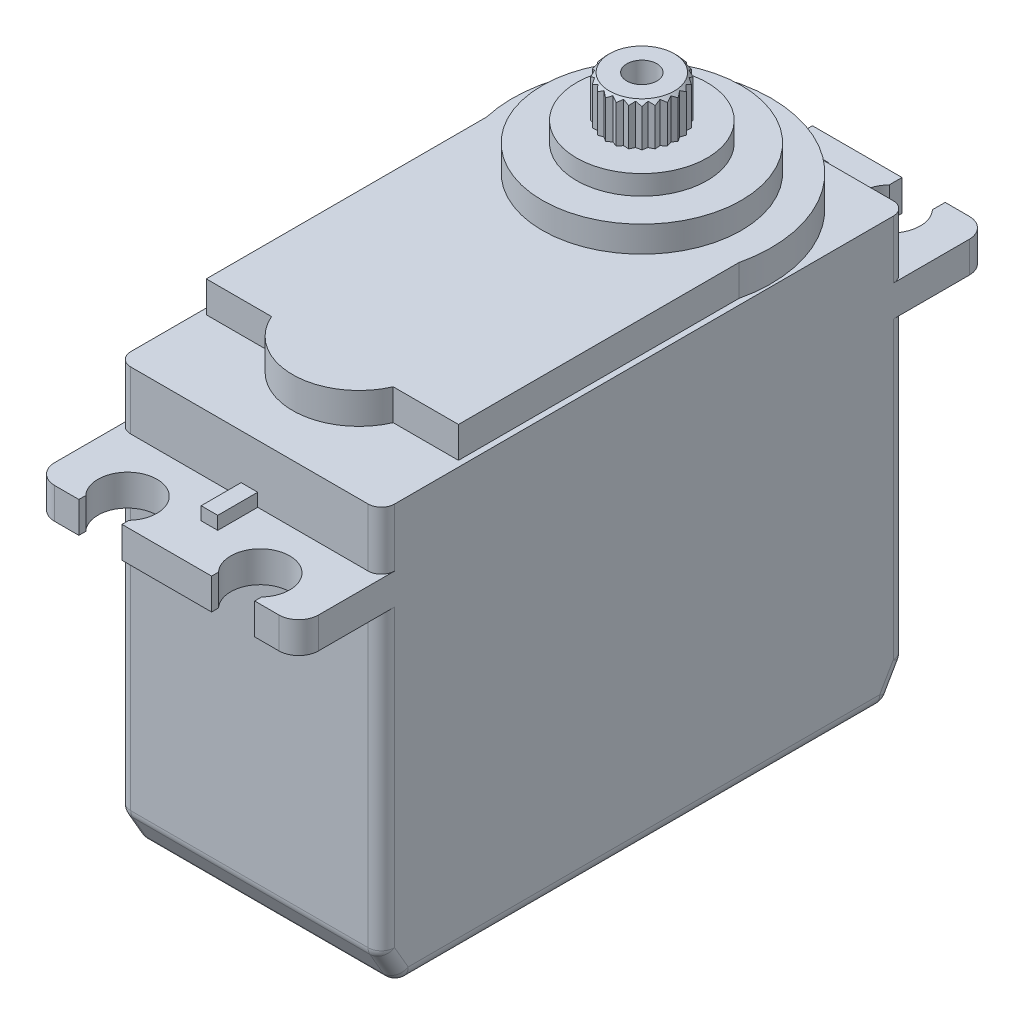
SolidWorks part; units mm, degrees
other "Camera1"
other "Camera2"
other "Camera3"
ref_plane "Front Plane" through (0, 0, 0) normal (0, 0, 1) x (1, 0, 0)
ref_plane "Top Plane" through (0, 0, 0) normal (0, 1, 0) x (1, 0, 0)
ref_plane "Right Plane" through (0, 0, 0) normal (1, 0, 0) x (0, 0, -1)
sketch "Sketch1" plane through (0, 0, 0) normal (0, 1, 0) x (1, 0, 0)
  line L1 (-10.1, 10.16) -> (10.1, 10.16)
  line L2 (-10.1, 10.16) -> (-10.1, -30.04)
  line L3 (-10.1, -30.04) -> (10.1, -30.04)
  line L4 (10.1, 10.16) -> (10.1, -30.04)
  point P4 (0, 10.16)
  dimension "D1" = 20.2
  dimension "D2" = 40.2
  dimension "D4" = 10.16
extrude "Extrude1" add sketch "Sketch1" along normal blind 25.4
sketch "Sketch2" plane through (0, 25.4, 0) normal (0, 1, 0) x (-1, 0, 0)
  line L0 (10.1, 30.04) -> (10.1, 36.3646)
  line L1 (10.1, 36.3646) -> (6.731, 36.3646)
  line L2 (-10.1, 36.3646) -> (-10.1, 30.04)
  line L3 (10.1, -10.16) -> (10.1, -16.4846)
  line L4 (10.1, -10.16) -> (10.1, 30.04)
  line L5 (10.1, 30.04) -> (-10.1, 30.04)
  line L6 (-10.1, 30.04) -> (-10.1, -10.16)
  line L7 (-10.1, -10.16) -> (10.1, -10.16)
  line L8 (10.1, -10.16) -> (10.1, 30.04)
  line L9 (10.1, 30.04) -> (-10.1, 30.04)
  line L10 (-10.1, 30.04) -> (-10.1, -10.16)
  line L11 (-10.1, -10.16) -> (10.1, -10.16)
  line L12 (10.1, -16.4846) -> (6.731, -16.4846)
  line L13 (-10.1, -16.4846) -> (-10.1, -10.16)
  line L14 (-6.731, 35.8342) -> (-6.731, 36.3646)
  line L15 (-3.429, 35.8342) -> (-3.429, 36.3646)
  line L16 (3.429, 35.8342) -> (3.429, 36.3646)
  line L17 (6.731, 35.8342) -> (6.731, 36.3646)
  line L18 (6.731, -15.5142) -> (6.731, -16.4846)
  line L19 (3.429, -15.5142) -> (3.429, -16.4846)
  line L20 (-3.429, -15.5142) -> (-3.429, -16.4846)
  line L21 (-6.731, -15.5142) -> (-6.731, -16.4846)
  line L22 (-6.731, -16.4846) -> (-10.1, -16.4846)
  line L23 (3.429, -16.4846) -> (-3.429, -16.4846)
  line L24 (-6.731, 36.3646) -> (-10.1, 36.3646)
  line L25 (3.429, 36.3646) -> (-3.429, 36.3646)
  arc A0 (3.429, 35.8342) -> (6.731, 35.8342) centre (5.08, 34.29) ccw
  arc A1 (-6.731, 35.8342) -> (-3.429, 35.8342) centre (-5.08, 34.29) ccw
  arc A2 (-3.429, -15.5142) -> (-6.731, -15.5142) centre (-5.08, -13.97) ccw
  arc A3 (6.731, -15.5142) -> (3.429, -15.5142) centre (5.08, -13.97) ccw
  line M5 (10.1, -10.16) -> (10.1, 30.04)
  line M6 (10.1, 30.04) -> (-10.1, 30.04)
  line M7 (-10.1, 30.04) -> (-10.1, -10.16)
  line M8 (-10.1, -10.16) -> (10.1, -10.16)
  dimension "D2" = 4.5212
  dimension "D9" = 3.302
  dimension "D3" = 5.08
  dimension "D4" = 10.16
  dimension "D5" = 48.26
  dimension "D6" = 3.81
  dimension "D7" = 6.3246
  dimension "D8" = 6.3246
  dimension "D10" = 3.302
  dimension "D11" = 1.651
  dimension "D12" = 1.651
  dimension "D1" = 0
extrude "Extrude2" add sketch "Sketch2" along normal blind 2.3813 contours M8 M5 M6 M7 | A3 L18 L12 L3 L13 L22 L21 A2 L20 L23 L19 M8 | A1 L14 L24 L2 L0 L1 L17 A0 L16 L25 L15 M6
sketch "Sketch3" plane through (0, 27.7812, 0) normal (0, 1, 0) x (-1, 0, 0)
  line L4 (10.1, -10.16) -> (10.1, 30.04)
  line L5 (-10.1, -10.16) -> (10.1, -10.16)
  line L6 (-10.1, 30.04) -> (-10.1, -10.16)
  line L7 (10.1, 30.04) -> (-10.1, 30.04)
  line L8 (10.1, -10.16) -> (10.1, 30.04)
  line L9 (-10.1, -10.16) -> (10.1, -10.16)
  line L10 (-10.1, 30.04) -> (-10.1, -10.16)
  line L11 (10.1, 30.04) -> (-10.1, 30.04)
  dimension "D1" = 0
extrude "Extrude3" add sketch "Sketch3" along normal blind 4.445
sketch "Sketch4" plane through (0, 32.2263, 0) normal (0, 1, 0) x (-1, 0, 0)
  line L0 (9.652, 2.2288) -> (9.652, 23.69)
  line L1 (9.652, 23.69) -> (4.6559, 23.69)
  line L2 (-9.652, 23.69) -> (-9.652, 2.2288)
  line L3 (10.1, 30.04) -> (-10.1, 30.04) construction
  line L4 (-4.6559, 23.69) -> (-9.652, 23.69)
  arc A0 (-9.652, 2.2288) -> (9.652, 2.2288) centre (0, 0) ccw
  arc A1 (4.6559, 23.69) -> (-4.6559, 23.69) centre (0, 21.658) ccw
  dimension "D1" = 19.812
  dimension "D5" = 5.08
  dimension "D2" = 6.35
  dimension "D3" = 19.304
  dimension "D4" = 9.652
  dimension "D6" = 2.032
extrude "Extrude4" add sketch "Sketch4" along normal blind 2.3813
ref_plane "Plane1" through (0, 38.1, 0) normal (0, -1, 0) x (1, 0, 0)
sketch "Sketch5" plane through (0, 34.6075, 0) normal (0, 1, 0) x (-1, 0, 0)
  circle A0 centre (0, 0) radius 7.62
  dimension "D1" = 15.24
extrude "Extrude5" add sketch "Sketch5" along normal up to surface (3.4925 mm away) up to plane "Plane1"
sketch "Sketch7" plane through (0, 0, 0) normal (1, 0, 0) x (0, 0, -1)
  line L0 (13.66, 28.7812) -> (13.66, 27.7812)
  line L4 (13.66, 28.7812) -> (10.16, 28.7812)
  line L5 (10.16, 32.2263) -> (10.16, 27.7812) construction
  line L6 (16.4846, 27.7812) -> (10.16, 27.7812) construction
  line L7 (10.16, 28.7812) -> (10.16, 27.7812)
  line L8 (10.16, 27.7812) -> (13.66, 27.7812)
  dimension "D1" = 1
  dimension "D2" = 3.5
extrude "Extrude6" add sketch "Sketch7" along normal mid plane 1.27
ref_plane "Plane2" through (0, 0, 9.72) normal (0, 0, 1) x (1, 0, 0)
mirror "Mirror1" about plane through (0, 0, 9.72) normal (0, 0, 1) of "Extrude6"
sketch "Sketch8" plane through (0, 38.1, 0) normal (0, 1, 0) x (-1, 0, 0)
  circle A0 centre (0, 0) radius 2.7781
  dimension "D1" = 5.5562
extrude "Extrude7" add sketch "Sketch8" along normal blind 3.175
chamfer "Chamfer2" distance 2.54 angle 30 2 edges at (0, 0, 30.04) (0, 0, -10.16)
fillet "Fillet1" radius 1.016 18 edges at (10.1, 0, 9.94) (10.1, 1.27, -9.4268) (0, 0, -8.6935) (0, 2.54, -10.16) (-10.1, 1.27, -9.4268) (10.1, 1.27, 29.3068) (0, 2.54, 30.04) (-10.1, 0, 9.94) (0, 0, 28.5735) (-10.1, 1.27, 29.3068)
fillet "Fillet2" radius 1.524 4 edges at (-10.1, 26.5906, 36.3646) (10.1, 26.5906, 36.3646) (-10.1, 26.5906, -16.4846) (10.1, 26.5906, -16.4846)
sketch "Sketch9" plane through (0, 0, -10.16) normal (0, 0, -1) x (-1, 0, 0)
  line L1 (-3.175, 5.588) -> (3.175, 5.588)
  line L2 (-3.175, 5.588) -> (-3.175, 3.048)
  line L3 (-3.175, 3.048) -> (3.175, 3.048)
  line L4 (3.175, 5.588) -> (3.175, 3.048)
  dimension "D1" = 6.35
  dimension "D2" = 2.54
  dimension "D3" = 3.048
  dimension "D4" = 3.175
extrude "Extrude8" add sketch "Sketch9" along normal blind 2.3813
sketch "Sketch10" plane through (0, 0, -12.5413) normal (0, 0, -1) x (-1, 0, 0)
  line L8 (-2.54, 4.953) -> (-2.54, 3.683)
  line L9 (-2.54, 3.683) -> (2.54, 3.683)
  line L10 (2.54, 3.683) -> (2.54, 4.953)
  line L11 (2.54, 4.953) -> (-2.54, 4.953)
  line L12 (-2.54, 4.953) -> (-2.54, 3.683)
  line L13 (-2.54, 3.683) -> (2.54, 3.683)
  line L14 (2.54, 3.683) -> (2.54, 4.953)
  line L15 (2.54, 4.953) -> (-2.54, 4.953)
  dimension "D1" = 0.635
extrude "Cut-Extrude1" cut sketch "Sketch10" against normal up to surface (2.3813 mm away) up to face at (2.271, 14.1061, -10.16)
chamfer "Chamfer3" distance 0.3 angle 45 1 edges at (0, 41.275, 2.7781)
sketch "Sketch11" plane through (0, 41.275, 0) normal (0, 1, 0) x (1, 0, 0)
  line L0 (0, -2.7781) -> (0, 0) construction
  line L1 (0, 0) -> (-0.719, -2.6835) construction
  line L2 (0, -2.7781) -> (-0.3365, -2.5561)
  line L3 (-0.3365, -2.5561) -> (-0.719, -2.6835)
  line L4 (-0.3365, -2.5561) -> (0, 0) construction
  line L5 (-0.719, -2.6835) -> (-0.9866, -2.3819)
  line L6 (-0.9866, -2.3819) -> (-1.3891, -2.4059)
  line L7 (-1.3891, -2.4059) -> (-1.5695, -2.0454)
  line L8 (-1.5695, -2.0454) -> (-1.9644, -1.9644)
  line L9 (-1.9644, -1.9644) -> (-2.0454, -1.5695)
  line L10 (-2.0454, -1.5695) -> (-2.4059, -1.3891)
  line L11 (-2.4059, -1.3891) -> (-2.3819, -0.9866)
  line L12 (-2.3819, -0.9866) -> (-2.6835, -0.719)
  line L13 (-2.6835, -0.719) -> (-2.5561, -0.3365)
  line L14 (-2.5561, -0.3365) -> (-2.7781, 0)
  line L15 (-2.7781, 0) -> (-2.5561, 0.3365)
  line L16 (-2.5561, 0.3365) -> (-2.6835, 0.719)
  line L17 (-2.6835, 0.719) -> (-2.3819, 0.9866)
  line L18 (-2.3819, 0.9866) -> (-2.4059, 1.3891)
  line L19 (-2.4059, 1.3891) -> (-2.0454, 1.5695)
  line L20 (-2.0454, 1.5695) -> (-1.9644, 1.9644)
  line L21 (-1.9644, 1.9644) -> (-1.5695, 2.0454)
  line L22 (-1.5695, 2.0454) -> (-1.3891, 2.4059)
  line L23 (-1.3891, 2.4059) -> (-0.9866, 2.3819)
  line L24 (-0.9866, 2.3819) -> (-0.719, 2.6835)
  line L25 (-0.719, 2.6835) -> (-0.3365, 2.5561)
  line L26 (-0.3365, 2.5561) -> (0, 2.7781)
  line L27 (0, 2.7781) -> (0.3365, 2.5561)
  line L28 (0.3365, 2.5561) -> (0.719, 2.6835)
  line L29 (0.719, 2.6835) -> (0.9866, 2.3819)
  line L30 (0.9866, 2.3819) -> (1.3891, 2.4059)
  line L31 (1.3891, 2.4059) -> (1.5695, 2.0454)
  line L32 (1.5695, 2.0454) -> (1.9644, 1.9644)
  line L33 (1.9644, 1.9644) -> (2.0454, 1.5695)
  line L34 (2.0454, 1.5695) -> (2.4059, 1.3891)
  line L35 (2.4059, 1.3891) -> (2.3819, 0.9866)
  line L36 (2.3819, 0.9866) -> (2.6835, 0.719)
  line L37 (2.6835, 0.719) -> (2.5561, 0.3365)
  line L38 (2.5561, 0.3365) -> (2.7781, 0)
  line L39 (2.7781, 0) -> (2.5561, -0.3365)
  line L40 (2.5561, -0.3365) -> (2.6835, -0.719)
  line L41 (2.6835, -0.719) -> (2.3819, -0.9866)
  line L42 (2.3819, -0.9866) -> (2.4059, -1.3891)
  line L43 (2.4059, -1.3891) -> (2.0454, -1.5695)
  line L44 (2.0454, -1.5695) -> (1.9644, -1.9644)
  line L45 (1.9644, -1.9644) -> (1.5695, -2.0454)
  line L46 (1.5695, -2.0454) -> (1.3891, -2.4059)
  line L47 (1.3891, -2.4059) -> (0.9866, -2.3819)
  line L48 (0.9866, -2.3819) -> (0.719, -2.6835)
  line L49 (0.719, -2.6835) -> (0.3365, -2.5561)
  line L50 (0.3365, -2.5561) -> (0, -2.7781)
  circle A0 centre (0, 0) radius 2.7781 construction
  circle A1 centre (0, 0) radius 2.7781 construction
  circle A2 centre (0, 0) radius 2.5781 construction
  circle A4 centre (0, 0) radius 2.7781 construction
  circle A5 centre (0, 0) radius 3.7781
  dimension "D2" = 0.2
  dimension "D5" = 1
  dimension "D1" = 15
  dimension "D3" = 7.5
  dimension "D4" = 24
extrude "Cut-Extrude2" cut sketch "Sketch11" against normal up to surface (3.175 mm away) up to face at (0, 38.1, -7.62)
sketch "Sketch12" plane through (0, 41.275, 0) normal (0, 1, 0) x (1, 0, 0)
  circle A0 centre (0, 0) radius 1.15
  dimension "D1" = 2.3
extrude "Cut-Extrude3" cut sketch "Sketch12" against normal blind 3
sketch "Sketch13" plane through (0, 38.1, 0) normal (0, 1, 0) x (1, 0, 0)
  circle A0 centre (0, 0) radius 5
  circle A1 centre (0, 0) radius 7.62
  circle A2 centre (0, 0) radius 7.62 construction
  dimension "D1" = 10
extrude "Cut-Extrude4" cut sketch "Sketch13" against normal blind 1.5
